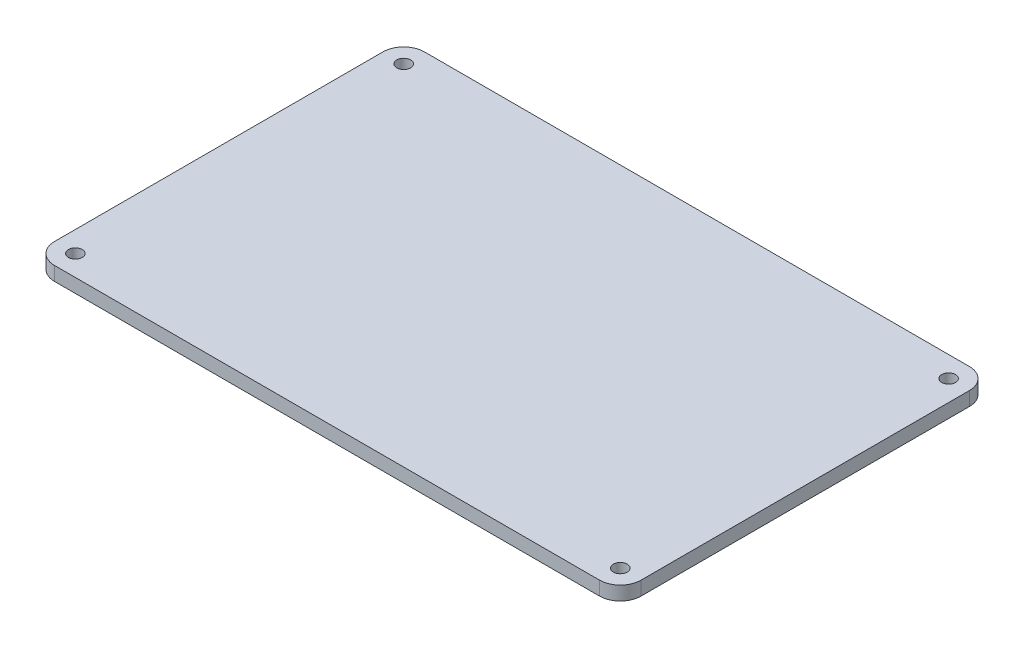
SolidWorks part; units mm, degrees
ref_plane "Front Plane" through (0, 0, 0) normal (0, 0, 1) x (1, 0, 0)
ref_plane "Top Plane" through (0, 0, 0) normal (0, 1, 0) x (1, 0, 0)
ref_plane "Right Plane" through (0, 0, 0) normal (1, 0, 0) x (0, 0, -1)
sketch "Sketch1" plane through (0, 0, 0) normal (0, 1, 0) x (1, 0, 0)
  line L8 (-66.6095, -5.2713) -> (-66.6095, 65.8287)
  line L9 (-62.1095, 70.3287) -> (55.8905, 70.3287)
  line L10 (60.3905, 65.8287) -> (60.3905, -5.2713)
  line L11 (-62.1095, -9.7713) -> (55.8905, -9.7713)
  circle A0 centre (-62.1095, 65.8287) radius 1.5
  circle A2 centre (55.8905, 65.8287) radius 1.5
  circle A4 centre (-62.1095, -5.2713) radius 1.5
  circle A6 centre (55.8905, -5.2713) radius 1.5
  arc A8 (-62.1095, 70.3287) -> (-66.6095, 65.8287) centre (-62.1095, 65.8287) ccw
  arc A9 (60.3905, 65.8287) -> (55.8905, 70.3287) centre (55.8905, 65.8287) ccw
  arc A10 (55.8905, -9.7713) -> (60.3905, -5.2713) centre (55.8905, -5.2713) ccw
  arc A11 (-66.6095, -5.2713) -> (-62.1095, -9.7713) centre (-62.1095, -5.2713) ccw
extrude "Boss-Extrude1" add sketch "Sketch1" along normal blind 3
